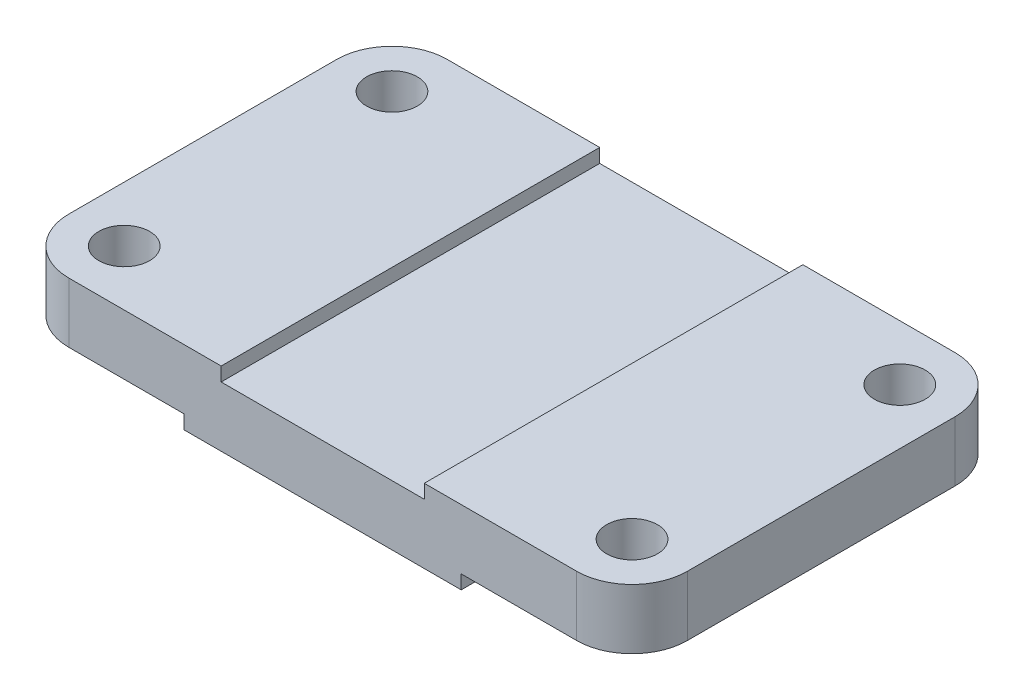
SolidWorks part; units mm, degrees
material "6063-T6"
ref_plane "Plan de face" through (0, 0, 0) normal (0, 0, 1) x (1, 0, 0)
ref_plane "Plan de dessus" through (0, 0, 0) normal (0, 1, 0) x (1, 0, 0)
ref_plane "Plan de droite" through (0, 0, 0) normal (1, 0, 0) x (0, 0, -1)
sketch "Esquisse1" plane through (0, 0, 0) normal (0, 0, 1) x (1, 0, 0)
  line L0 (22, 16) -> (67, 16)
  line L1 (-67, 16) -> (-22, 16)
  line L2 (-67, 16) -> (-67, 3)
  line L3 (-30, 0) -> (30, 0)
  line L4 (67, 16) -> (67, 3)
  line L6 (-22, 16) -> (-22, 13)
  line L7 (-22, 13) -> (22, 13)
  line L8 (22, 16) -> (22, 13)
  line L11 (67, 3) -> (30, 3)
  line L12 (30, 0) -> (30, 3)
  line L15 (-67, 3) -> (-30, 3)
  line L16 (-30, 0) -> (-30, 3)
  point P1 (0, 0)
  dimension "D1" = 3
  dimension "D2" = 3
  dimension "D3" = 16
  dimension "D4" = 45
  dimension "D5" = 60
  dimension "D6" = 134
extrude "Extrusion1" add sketch "Esquisse1" along normal mid plane 82
fillet "Congé1" radius 12 4 edges at (-67, 9.5, -41) (67, 9.5, -41) (67, 9.5, 41) (-67, 9.5, 41)
hole_wizard "Dégagement M1.61" positions "Esquisse3" profile "Esquisse2" hole size "M1.6" standard "Ansi Metric" end condition through all
sketch "Esquisse3" plane through (0, 16, 0) normal (0, 1, 0) x (-1, 0, 0)
  arc A0 (67, 29) -> (55, 41) centre (55, 29) ccw construction
  point P0 (55, 29)
  point P7 (55, -29)
  point P10 (-55, -29)
  point P13 (-55, 29)
sketch "Esquisse2" plane through (-55, 16, 29) normal (1, 0, 0) x (0, 0, 1)
  line L0 (0, 0) -> (0, 16)
  line L1 (0, 16) -> (5.5, 16)
  line L2 (5.5, 16) -> (5.5, 0)
  line L5 (5.5, 0) -> (0, 0)
  line L11 (0, -6.35) -> (0, 107.95) construction
  dimension "Diamètre du perçage jusqu'au prochain" = 11
  dimension "Profondeur du perçage jusqu'au prochain" = 16
